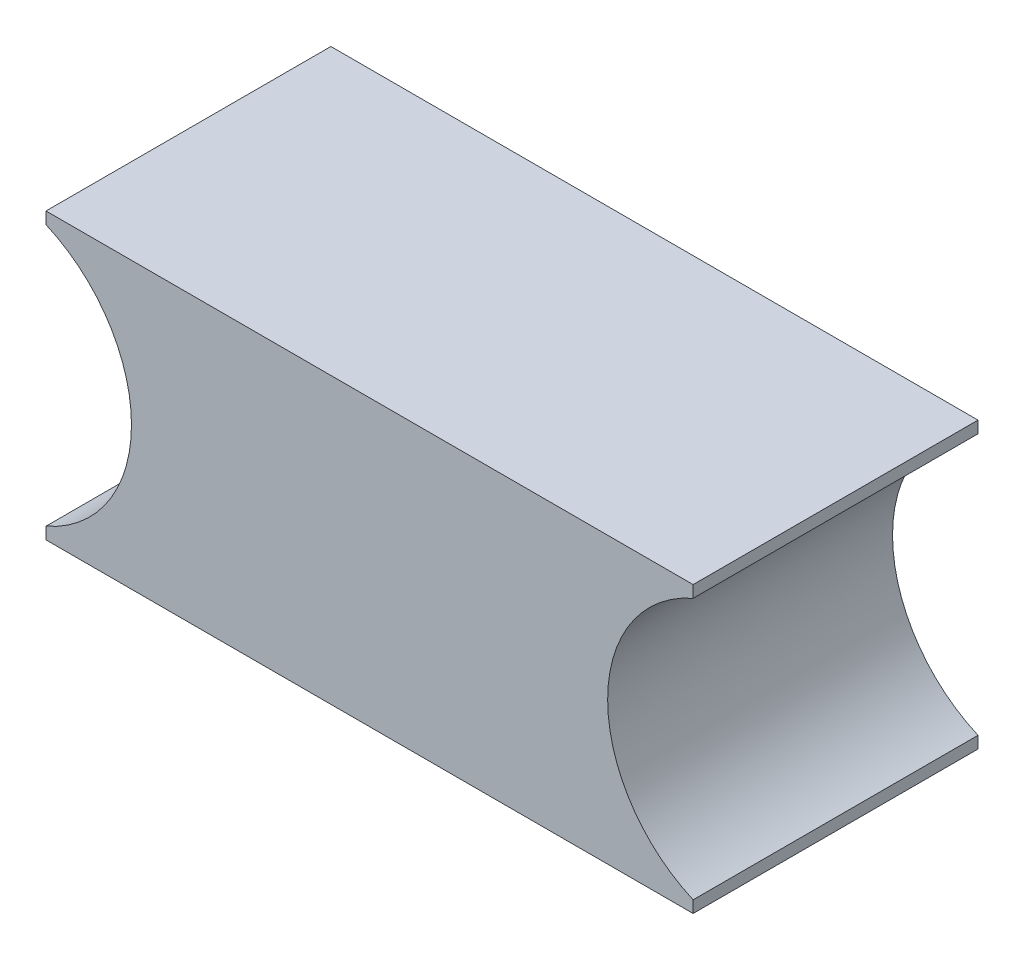
SolidWorks part; units mm, degrees
ref_plane "Front Plane" through (0, 0, 0) normal (0, 0, 1) x (1, 0, 0)
ref_plane "Top Plane" through (0, 0, 0) normal (0, 1, 0) x (1, 0, 0)
ref_plane "Right Plane" through (0, 0, 0) normal (1, 0, 0) x (0, 0, -1)
sketch "Sketch4" plane through (0, 0, 0) normal (0, 0, 1) x (1, 0, 0)
  line L0 (-3.6236, 25.4) -> (111.7743, 25.4)
  line L2 (111.7743, -25.4) -> (-3.6236, -25.4)
  line L3 (-3.6236, 25.4) -> (-3.6236, 23.2795)
  line L4 (111.7743, -23.2795) -> (111.7743, -25.4)
  line L5 (-3.6236, -23.2795) -> (-3.6236, -25.4)
  line L7 (111.7743, 25.4) -> (111.7743, 23.2795)
  arc A1 (-3.6236, 23.2795) -> (-3.6236, -23.2795) centre (-13.7836, 0) cw
  arc A3 (111.7743, 23.2795) -> (111.7743, -23.2795) centre (121.9343, 0) ccw
  point P3 (0, 0)
  point P5 (0, 0)
  point P11 (0, 0)
extrude "Boss-Extrude2" add sketch "Sketch4" along normal blind 50.8
